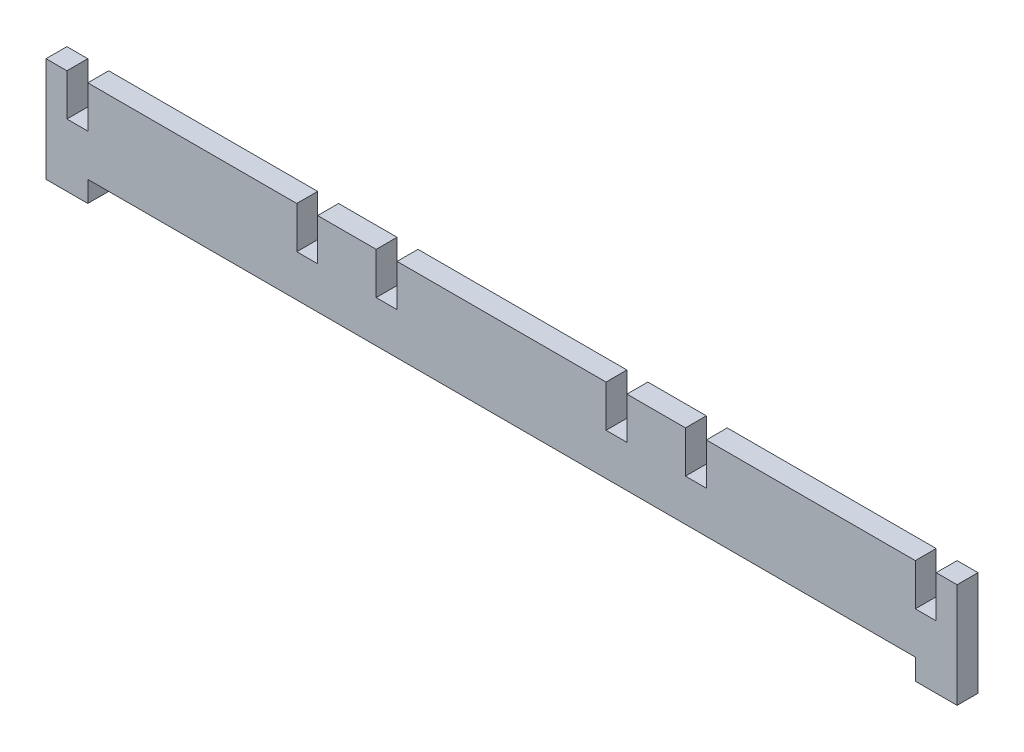
SolidWorks part; units mm, degrees
ref_plane "Plan de face" through (0, 0, 0) normal (0, 0, 1) x (1, 0, 0)
ref_plane "Plan de dessus" through (0, 0, 0) normal (0, 1, 0) x (1, 0, 0)
ref_plane "Plan de droite" through (0, 0, 0) normal (1, 0, 0) x (0, 0, -1)
sketch "Esquisse1" plane through (0, 0, 0) normal (0, 0, 1) x (1, 0, 0)
  line L0 (-30, 0) -> (-30, -10)
  line L1 (-30, -10) -> (-25, -10)
  line L2 (-25, -10) -> (-25, 0)
  line L3 (-25, 0) -> (25, 0)
  line L5 (-109, 0) -> (-109, -25)
  line L6 (-109, -25) -> (-99, -25)
  line L7 (-99, -25) -> (-99, -20)
  line L8 (-99, -20) -> (99, -20)
  line L9 (0, 0) -> (0, -20) construction
  line L10 (99, -25) -> (99, -20)
  line L11 (109, -25) -> (99, -25)
  line L12 (109, 0) -> (109, -25)
  line L14 (30, 0) -> (30, -10)
  line L15 (30, -10) -> (25, -10)
  line L16 (25, -10) -> (25, 0)
  line L17 (104, 0) -> (104, -10)
  line L18 (104, -10) -> (99, -10)
  line L19 (99, -10) -> (99, 0)
  line L20 (49, 0) -> (99, 0)
  line L21 (49, -10) -> (49, 0)
  line L22 (44, -10) -> (49, -10)
  line L23 (44, 0) -> (44, -10)
  line L24 (-44, 0) -> (-44, -10)
  line L25 (-44, -10) -> (-49, -10)
  line L26 (-49, -10) -> (-49, 0)
  line L27 (-99, 0) -> (-49, 0)
  line L28 (-99, -10) -> (-99, 0)
  line L29 (-104, -10) -> (-99, -10)
  line L30 (-104, 0) -> (-104, -10)
  line L31 (-44, 0) -> (-30, 0)
  line L32 (30, 0) -> (44, 0)
  line L33 (104, 0) -> (109, 0)
  line L34 (-109, 0) -> (-104, 0)
  dimension "D1" = 25
  dimension "D2" = 10
  dimension "D3" = 10
  dimension "D4" = 5
  dimension "D5" = 10
  dimension "D6" = 5
  dimension "D8" = 74
  dimension "D11" = 74
  dimension "D12" = 5
  dimension "D9" = 2
  dimension "D10" = 2
extrude "Boss.-Extru.1" add sketch "Esquisse1" along normal blind 5
